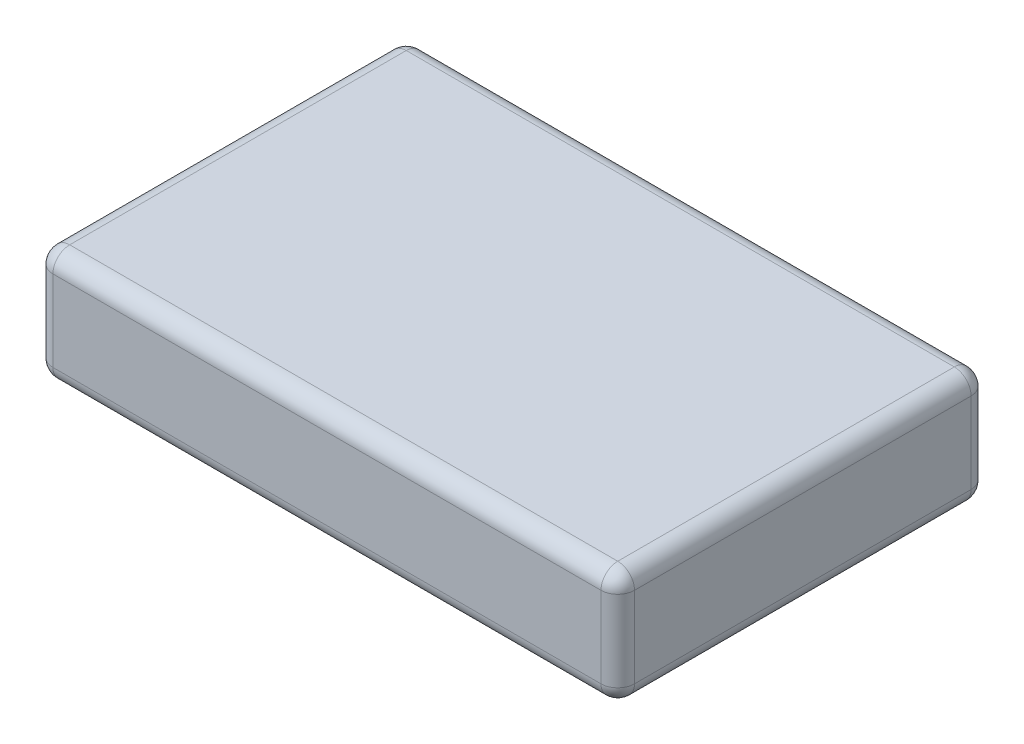
SolidWorks part; units mm, degrees
material "Silicon"
ref_plane "Front Plane" through (0, 0, 0) normal (0, 0, 1) x (1, 0, 0)
ref_plane "Top Plane" through (0, 0, 0) normal (0, 1, 0) x (1, 0, 0)
ref_plane "Right Plane" through (0, 0, 0) normal (1, 0, 0) x (0, 0, -1)
sketch "Sketch1" plane through (0, 0, 0) normal (0, 1, 0) x (1, 0, 0)
  line L1 (-33, -21) -> (33, -21)
  line L2 (-33, -21) -> (-33, 21)
  line L3 (-33, 21) -> (33, 21)
  line L4 (33, -21) -> (33, 21)
  line L5 (-33, -21) -> (33, 21) construction
  line L6 (-33, 21) -> (33, -21) construction
  point P0 (0, 0)
  dimension "D1" = 66
  dimension "D2" = 42
extrude "Boss-Extrude1" add sketch "Sketch1" along normal blind 13
fillet "Fillet1" radius 1.905 12 edges at (0, 0, -21) (0, 13, -21) (33, 13, 0) (33, 6.5, -21) (33, 0, 0) (0, 13, 21) (33, 6.5, 21) (0, 0, 21) (-33, 6.5, -21) (-33, 13, 0) (-33, 6.5, 21) (-33, 0, 0)
